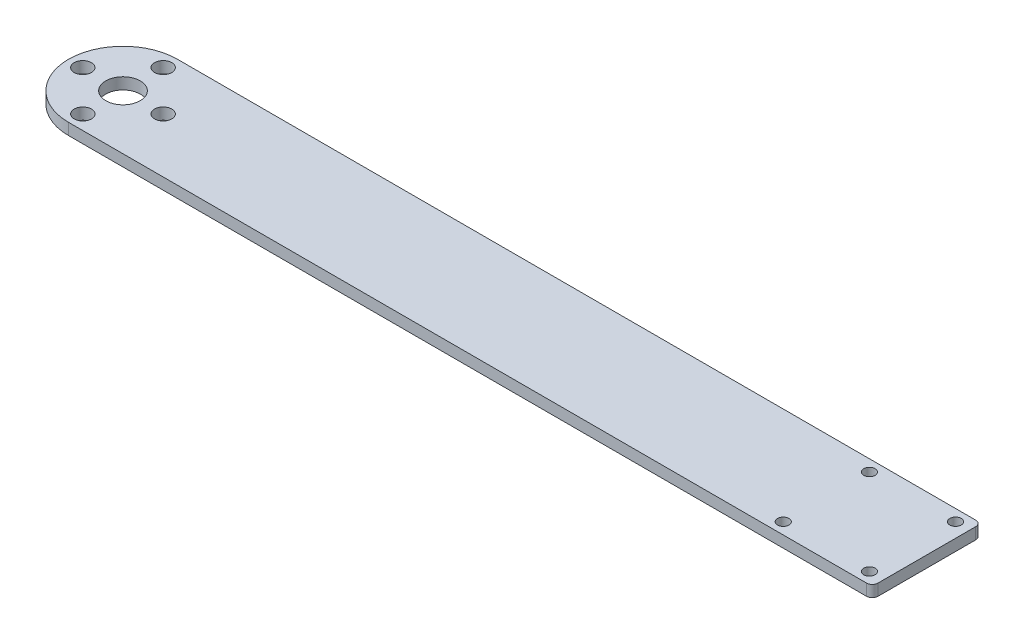
SolidWorks part; units mm, degrees
ref_plane "Спереди" through (0, 0, 0) normal (0, 0, 1) x (1, 0, 0)
ref_plane "Сверху" through (0, 0, 0) normal (0, 1, 0) x (1, 0, 0)
ref_plane "Справа" through (0, 0, 0) normal (1, 0, 0) x (0, 0, -1)
sketch "Эскиз1" plane through (0, 0, 0) normal (0, 1, 0) x (1, 0, 0)
  line L0 (0, 9.5) -> (140, 9.5)
  line L1 (0, -9.5) -> (140, -9.5)
  line L2 (140, -9.5) -> (140, 9.5)
  line L8 (137.5, 7.5) -> (122.5, 7.5) construction
  line L9 (137.5, 7.5) -> (137.5, -7.5) construction
  line L10 (137.5, -7.5) -> (122.5, -7.5) construction
  line L11 (122.5, 7.5) -> (122.5, -7.5) construction
  arc A0 (0, 9.5) -> (0, -9.5) centre (0, 0) ccw
  circle A1 centre (0, 0) radius 7 construction
  circle A2 centre (0, 7) radius 1.5
  circle A3 centre (7, 0) radius 1.5
  circle A4 centre (0, -7) radius 1.5
  circle A5 centre (-7, 0) radius 1.5
  circle A6 centre (122.5, 7.5) radius 1
  circle A7 centre (137.5, 7.5) radius 1
  circle A8 centre (122.5, -7.5) radius 1
  circle A9 centre (137.5, -7.5) radius 1
  circle A10 centre (0, 0) radius 8.5 construction
  circle A11 centre (0, 0) radius 3
  point P28 (140, 0)
  dimension "D1" = 14
  dimension "D2" = 3
  dimension "D3" = 19
  dimension "D4" = 140
  dimension "D5" = 2
  dimension "D6" = 6
  dimension "D8" = 2.5
  dimension "D9" = 7.5
  dimension "D10" = 15
extrude "Бобышка-Вытянуть1" add sketch "Эскиз1" along normal blind 2
fillet "Скругление1" radius 1 2 edges at (140, 1, 9.5) (140, 1, -9.5)
